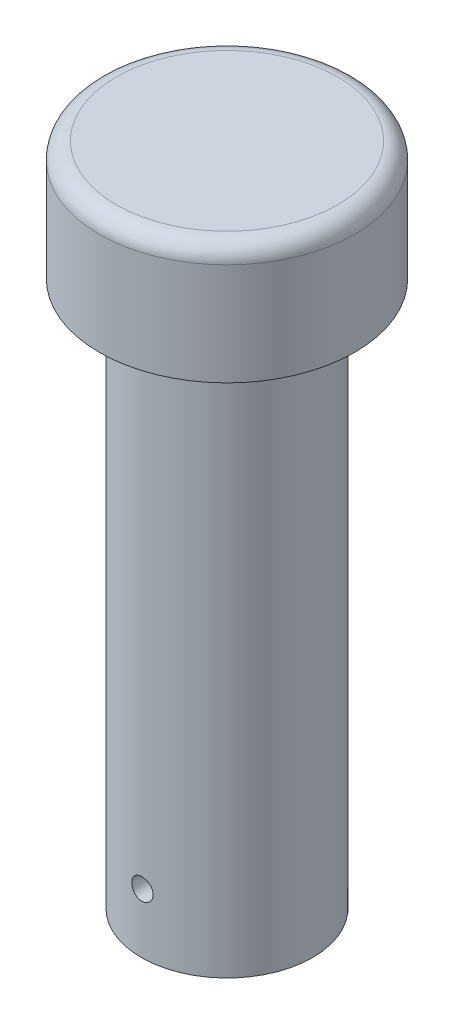
SolidWorks part; units mm, degrees
ref_plane "Front Plane" through (0, 0, 0) normal (0, 0, 1) x (1, 0, 0)
ref_plane "Top Plane" through (0, 0, 0) normal (0, 1, 0) x (1, 0, 0)
ref_plane "Right Plane" through (0, 0, 0) normal (1, 0, 0) x (0, 0, -1)
sketch "Sketch1" plane through (0, 0, 0) normal (0, 0, 1) x (1, 0, 0)
  line L0 (0, 0) -> (0, 78)
  line L1 (0, 0) -> (10.049, 0)
  line L2 (0, 78) -> (15, 78)
  line L3 (15, 78) -> (15, 74)
  line L4 (15, 74) -> (0, 74)
  line L5 (15, 74) -> (15, 64)
  line L6 (15, 64) -> (10.049, 64)
  line L7 (10.049, 64) -> (10.049, 0)
  dimension "D1" = 15
  dimension "D2" = 4
  dimension "D3" = 10
  dimension "D4" = 64
  dimension "D5" = 78
revolve "Revolve2" add sketch "Sketch1" angle 360 about L0
fillet "Fillet3" radius 2 1 edges at (15, 78, 0)
sketch "Sketch2" plane through (0, 0, 0) normal (0, 0, 1) x (1, 0, 0)
  line L0 (-10.049, 0) -> (10.049, 0) construction
  line L1 (10.049, 0) -> (10.049, 64) construction
  circle A0 centre (0.049, 7) radius 1.25
  dimension "D1" = 2.5
  dimension "D2" = 7
  dimension "D3" = 10
extrude "Cut-Extrude1" cut sketch "Sketch2" along normal through all both and the other way through all
